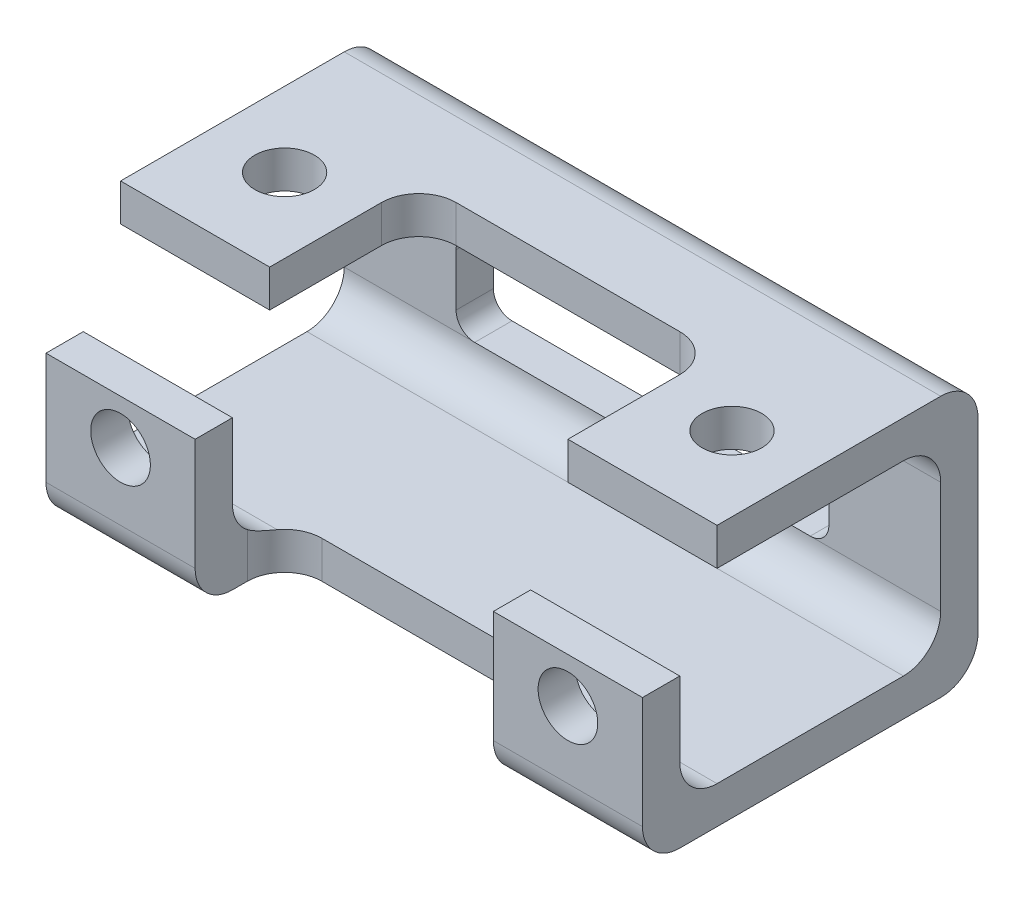
SolidWorks part; units mm, degrees
ref_plane "Front Plane" through (0, 0, 0) normal (0, 0, 1) x (1, 0, 0)
ref_plane "Top Plane" through (0, 0, 0) normal (0, 1, 0) x (1, 0, 0)
ref_plane "Right Plane" through (0, 0, 0) normal (1, 0, 0) x (0, 0, -1)
sketch "Sketch1" plane through (0, 0, 0) normal (1, 0, 0) x (0, 0, -1)
  line L0 (-40, 20) -> (-40, 5)
  line L1 (-35, 0) -> (0, 0)
  line L2 (5, 5) -> (5, 30)
  line L3 (0, 35) -> (-30, 35)
  line L4 (-30, 35) -> (-30, 30)
  line L5 (-30, 30) -> (-5, 30)
  line L6 (0, 25) -> (0, 10)
  line L7 (-5, 5) -> (-30, 5)
  line L8 (-35, 10) -> (-35, 20)
  line L9 (-35, 20) -> (-40, 20)
  arc A0 (-35, 10) -> (-30, 5) centre (-30, 10) ccw
  arc A1 (5, 30) -> (0, 35) centre (0, 30) ccw
  arc A2 (-40, 5) -> (-35, 0) centre (-35, 5) ccw
  arc A3 (0, 25) -> (-5, 30) centre (-5, 25) ccw
  arc A5 (-5, 5) -> (0, 10) centre (-5, 10) ccw
  arc A6 (0, 0) -> (5, 5) centre (0, 5) ccw
  point P1 (5, 17.5)
  point P2 (0.2942, 22.9091)
  point P11 (0, 0)
  point P14 (9.8594, 44.4)
  point P16 (-25.2745, 19.4)
  point P18 (3.6, 39.1244)
  point P22 (0, 0)
  point P24 (-36.3156, 32.9102)
  point P27 (3.6, 24.1244)
  point P30 (8.6, 19.9846)
  point P32 (0, 0)
  point P33 (0, 0)
  dimension "D8" = 5
  dimension "D5" = 10
  dimension "D1" = 35
  dimension "D2" = 35
  dimension "D3" = 45
  dimension "D4" = 20
  dimension "D6" = 5
  dimension "D7" = 5
extrude "Boss-Extrude1" add sketch "Sketch1" along normal blind 80
sketch "Sketch2" plane through (0, 0, -5) normal (0, 0, -1) x (-1, 0, 0)
  line L0 (-62.5, 22) -> (-17.5, 22)
  line L1 (-62.5, 10) -> (-17.5, 10)
  line L2 (-65, 19.5) -> (-65, 12.5)
  line L3 (-15, 19.5) -> (-15, 12.5)
  line L4 (0, 5) -> (0, 30) construction
  line L5 (-80, 0) -> (0, 0) construction
  arc A0 (-62.5, 22) -> (-65, 19.5) centre (-62.5, 19.5) ccw
  arc A1 (-15, 19.5) -> (-17.5, 22) centre (-17.5, 19.5) ccw
  arc A2 (-65, 12.5) -> (-62.5, 10) centre (-62.5, 12.5) ccw
  arc A3 (-17.5, 10) -> (-15, 12.5) centre (-17.5, 12.5) ccw
  dimension "D1" = 5
  dimension "D2" = 12
  dimension "D3" = 50
  dimension "D4" = 15
  dimension "D5" = 10
extrude "Cut-Extrude1" cut sketch "Sketch2" against normal up to next
sketch "Sketch4" plane through (0, 35, 0) normal (0, 1, 0) x (1, 0, 0)
  line L0 (20, -40) -> (20, -33)
  line L1 (80, -40) -> (0, -40) construction
  line L2 (25, -28) -> (55, -28)
  line L3 (60, -33) -> (60, -40)
  line L4 (0, -30) -> (0, -35) construction
  line L5 (20, -40) -> (60, -40)
  arc A0 (25, -28) -> (20, -33) centre (25, -33) ccw
  arc A1 (60, -33) -> (55, -28) centre (55, -33) ccw
  dimension "D4" = 10
  dimension "D1" = 12
  dimension "D2" = 40
  dimension "D3" = 20
extrude "Cut-Extrude2" cut sketch "Sketch4" against normal blind 80
sketch "Sketch5" plane through (0, 35, 0) normal (0, 1, 0) x (1, 0, 0)
  line L0 (20, -30) -> (21, -30)
  line L1 (21, -30) -> (0, -30) construction
  line L2 (0, 0) -> (0, -30) construction
  line L3 (80, 0) -> (80, -30) construction
  line L4 (80, -30) -> (59, -30) construction
  line L5 (20, -15) -> (20, -30)
  line L6 (25, -10) -> (55, -10)
  line L7 (60, -15) -> (60, -30)
  line L8 (21, -30) -> (0, -30) construction
  line L9 (25, -28) -> (55, -28)
  line L10 (59, -30) -> (60, -30)
  circle A0 centre (10, -18) radius 4
  circle A1 centre (70, -18) radius 4
  arc A2 (25, -10) -> (20, -15) centre (25, -15) ccw
  arc A3 (60, -15) -> (55, -10) centre (55, -15) ccw
  arc A4 (21, -30) -> (25, -28) centre (25, -33) cw
  arc A5 (25, -28) -> (21, -30) centre (25, -33) ccw construction
  arc A6 (55, -28) -> (59, -30) centre (55, -33) cw
  arc A7 (59, -30) -> (55, -28) centre (55, -33) ccw construction
  dimension "D1" = 8
  dimension "D9" = 10
  dimension "D2" = 12
  dimension "D3" = 10
  dimension "D4" = 10
  dimension "D5" = 12
  dimension "D6" = 20
  dimension "D7" = 40
  dimension "D8" = 20
extrude "Cut-Extrude3" cut sketch "Sketch5" against normal up to next
sketch "Sketch6" plane through (0, 0, 40) normal (0, 0, 1) x (1, 0, 0)
  line L0 (0, 20) -> (0, 5) construction
  line L1 (20, 0) -> (0, 0) construction
  line L2 (80, 20) -> (80, 5) construction
  line L4 (80, 0) -> (60, 0) construction
  circle A0 centre (10, 14) radius 4
  circle A1 centre (70, 14) radius 4
  point P8 (69.4636, 14)
  point P9 (0, 0)
  point P14 (65.9891, -0.8453)
  dimension "D1" = 8
  dimension "D2" = 10
  dimension "D3" = 14
  dimension "D4" = 10
  dimension "D5" = 14
extrude "Cut-Extrude4" cut sketch "Sketch6" against normal up to next
